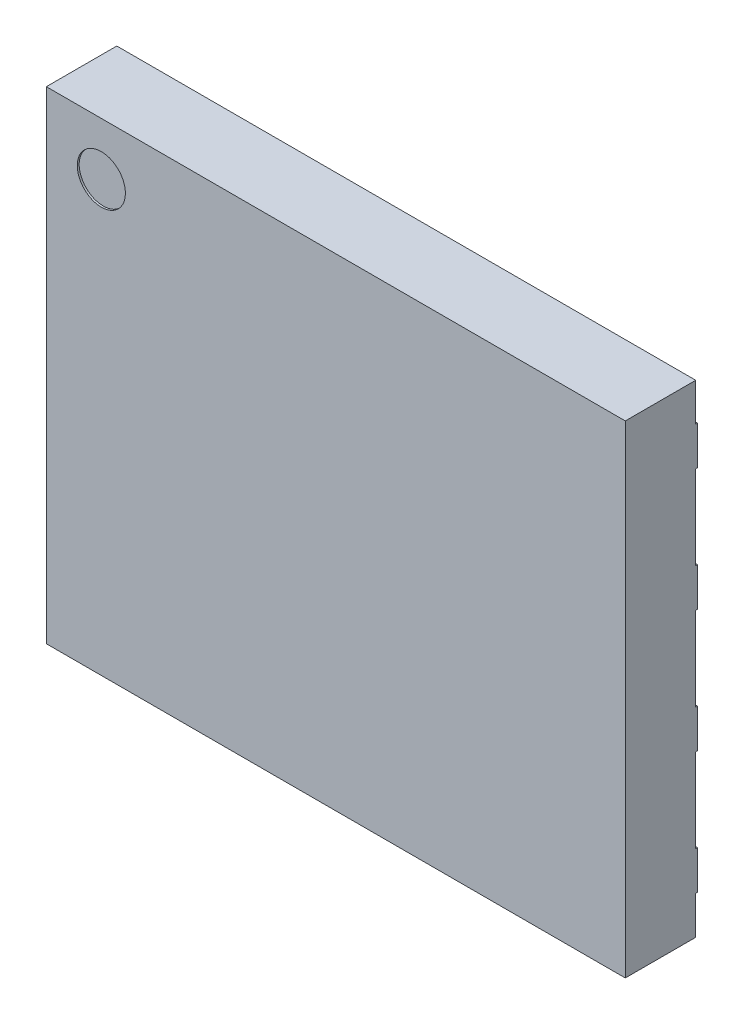
SolidWorks part; units mm, degrees
ref_plane "Front Plane" through (0, 0, 0) normal (0, 0, 1) x (1, 0, 0)
ref_plane "Top Plane" through (0, 0, 0) normal (0, 1, 0) x (1, 0, 0)
ref_plane "Right Plane" through (0, 0, 0) normal (1, 0, 0) x (0, 0, -1)
sketch "Sketch1" plane through (0, 0, 0) normal (0, 0, 1) x (1, 0, 0)
  line L1 (3, -2.5) -> (-3, -2.5)
  line L2 (3, -2.5) -> (3, 2.5)
  line L3 (3, 2.5) -> (-3, 2.5)
  line L4 (-3, -2.5) -> (-3, 2.5)
  line L5 (3, -2.5) -> (-3, 2.5) construction
  line L6 (3, 2.5) -> (-3, -2.5) construction
  point P0 (0, 0)
  dimension "D1" = 5
  dimension "D2" = 6
extrude "Boss-Extrude1" add sketch "Sketch1" along normal blind 0.73 from offset 0.02
sketch "Sketch2" plane through (0, 0, 0.02) normal (0, 0, -1) x (-1, 0, 0)
  line L0 (-3, -2.5) -> (-3, 2.5) construction
  line L1 (-3, 2.105) -> (-2.6, 2.105)
  line L2 (-3, 2.105) -> (-3, 1.705)
  line L3 (-3, 1.705) -> (-2.6, 1.705)
  line L5 (-3, 1.905) -> (-2.4, 1.905) construction
  arc A0 (-2.6, 2.105) -> (-2.6, 1.705) centre (-2.6, 1.905) cw
  point P9 (-2.4, 1.905)
  point P10 (-2.4, 1.739)
  dimension "D1" = 0.6
  dimension "D2" = 0.4
  dimension "D3" = 1.905
extrude "Boss-Extrude2" add sketch "Sketch2" along normal blind 0.02
pattern_linear "LPattern1" count 4 spacing 1.27 along (0, -1, 0) of "Boss-Extrude2"
mirror "Mirror1" about plane through (0, 0, 0) normal (1, 0, 0) of "LPattern1", "Boss-Extrude2"
sketch "Sketch3" plane through (0, 0, 0.02) normal (0, 0, -1) x (-1, 0, 0)
  line L0 (1.7, 1.7156) -> (1.2656, 2.15)
  line L1 (-1.7, -2.15) -> (1.7, -2.15)
  line L2 (-1.7, -2.15) -> (-1.7, 2.15)
  line L3 (-1.7, 2.15) -> (1.2656, 2.15)
  line L4 (1.7, -2.15) -> (1.7, 1.7156)
  line L5 (-1.7, -2.15) -> (1.5082, 1.9074) construction
  line L6 (-1.7, 2.15) -> (1.7, -2.15) construction
  point P0 (0, 0)
  dimension "D1" = 4.3
  dimension "D2" = 3.4
extrude "Boss-Extrude3" add sketch "Sketch3" along normal blind 0.02
sketch "Sketch4" plane through (0, 0, 0.75) normal (0, 0, 1) x (1, 0, 0)
  circle A0 centre (-2.4303, 1.9528) radius 0.2494
extrude "Cut-Extrude1" cut sketch "Sketch4" against normal blind 0.02
